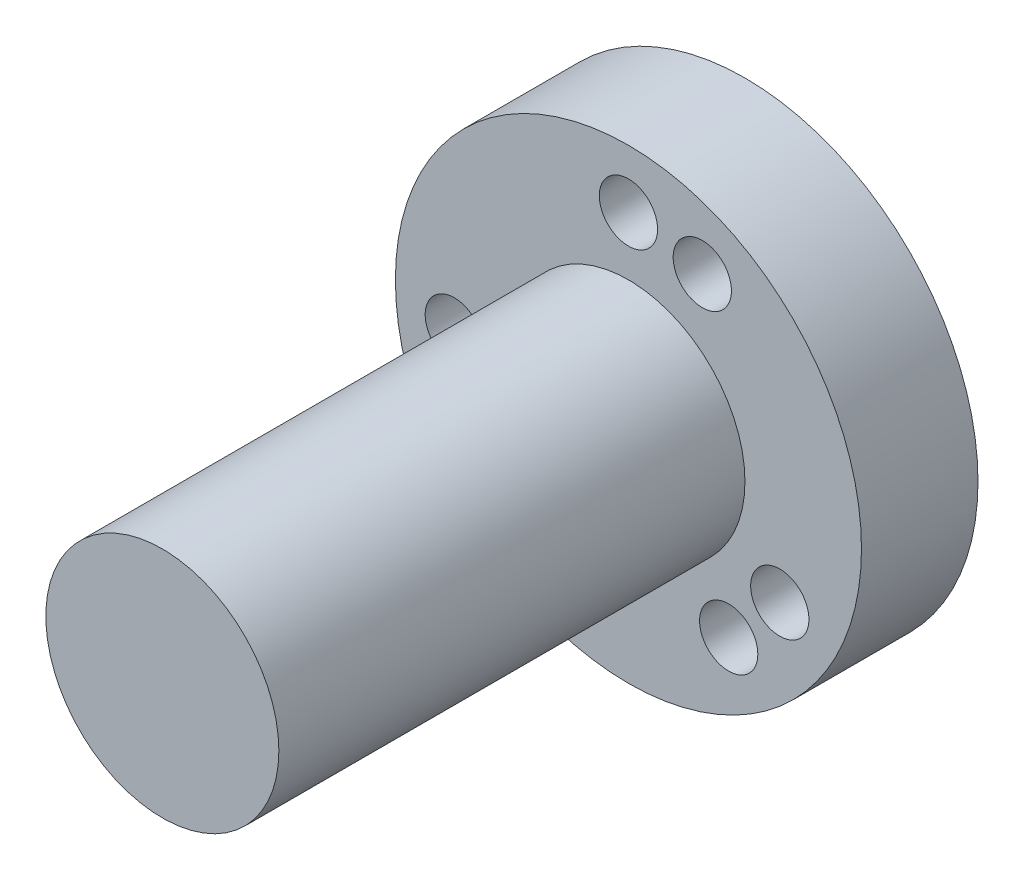
SolidWorks part; units mm, degrees
ref_plane "前视" through (0, 0, 0) normal (0, 0, 1) x (1, 0, 0)
ref_plane "上视" through (0, 0, 0) normal (0, 1, 0) x (1, 0, 0)
ref_plane "右视" through (0, 0, 0) normal (1, 0, 0) x (0, 0, -1)
sketch "草图1" plane through (0, 0, 0) normal (0, 0, 1) x (1, 0, 0)
  circle A0 centre (0, 0) radius 2.5
  dimension "D1" = 5
extrude "凸台-拉伸1" add sketch "草图1" along normal blind 1
sketch "草图2" plane through (0, 0, 1) normal (0, 0, 1) x (1, 0, 0)
  line L0 (0, 0) -> (2.5357, 5.4378) construction
  line L1 (0, 6) -> (0, 0) construction
  circle A0 centre (0, 0) radius 6
  circle A1 centre (0, 4.5) radius 0.75
  circle A2 centre (1.9018, 4.0784) radius 0.75
  circle A3 centre (3.8971, -2.25) radius 0.75
  circle A4 centre (2.5811, -3.6862) radius 0.75
  circle A5 centre (-3.8971, -2.25) radius 0.75
  circle A6 centre (-4.4829, -0.3922) radius 0.75
  point P19 (0, 0)
  dimension "D1" = 12
  dimension "D3" = 1.5
  dimension "D6" = 1.5
  dimension "D2" = 4.5
  dimension "D4" = 25
  dimension "D5" = 4.5
  dimension "D7" = 3
extrude "凸台-拉伸2" add sketch "草图2" along normal blind 3
sketch "草图3" plane through (0, 0, 4) normal (0, 0, 1) x (1, 0, 0)
  circle A0 centre (0, 0) radius 3
  dimension "D1" = 6
extrude "凸台-拉伸3" add sketch "草图3" along normal blind 12
